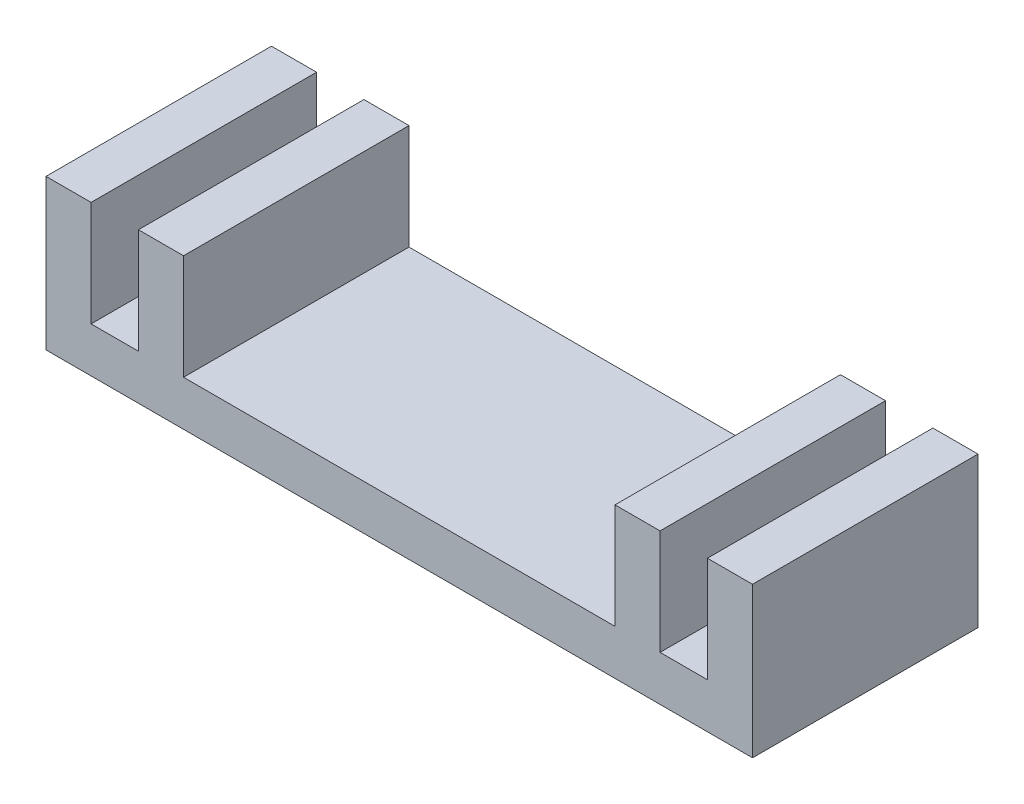
SolidWorks part; units mm, degrees
ref_plane "Płaszczyzna przednia" through (0, 0, 0) normal (0, 0, 1) x (1, 0, 0)
ref_plane "Płaszczyzna górna" through (0, 0, 0) normal (0, 1, 0) x (1, 0, 0)
ref_plane "Płaszczyzna prawa" through (0, 0, 0) normal (1, 0, 0) x (0, 0, -1)
sketch "Szkic1" plane through (0, 0, 0) normal (0, 0, 1) x (1, 0, 0)
  line L0 (20.5, 0) -> (-20.5, 0)
  line L1 (-20.5, 0) -> (-23.5, 0)
  line L2 (-23.5, 0) -> (-23.5, 10)
  line L3 (-23.5, 10) -> (-20.5, 10)
  line L4 (-20.5, 10) -> (-20.5, 3)
  line L5 (-20.5, 3) -> (-17.35, 3)
  line L6 (-17.35, 3) -> (-17.35, 10)
  line L7 (-17.35, 10) -> (-14.3512, 10)
  line L8 (-14.3512, 10) -> (-14.3512, 3)
  line L9 (-14.3512, 3) -> (14.3512, 3)
  line L10 (0, -7.6054) -> (0, 19.0885) construction
  line L12 (14.3512, 10) -> (14.3512, 3)
  line L13 (17.35, 10) -> (14.3512, 10)
  line L14 (17.35, 3) -> (17.35, 10)
  line L15 (20.5, 3) -> (17.35, 3)
  line L16 (20.5, 10) -> (20.5, 3)
  line L17 (23.5, 10) -> (20.5, 10)
  line L18 (23.5, 0) -> (23.5, 10)
  line L19 (20.5, 0) -> (23.5, 0)
  point P4 (0, 0)
  dimension "D1" = 41
  dimension "D2" = 3
  dimension "D3" = 10
  dimension "D4" = 3.15
  dimension "D5" = 7
  dimension "D6" = 3
  dimension "D7" = 7
  dimension "D8" = 2.9988
extrude "Dodanie-wyciągnięcie1" add sketch "Szkic1" along normal blind 15
